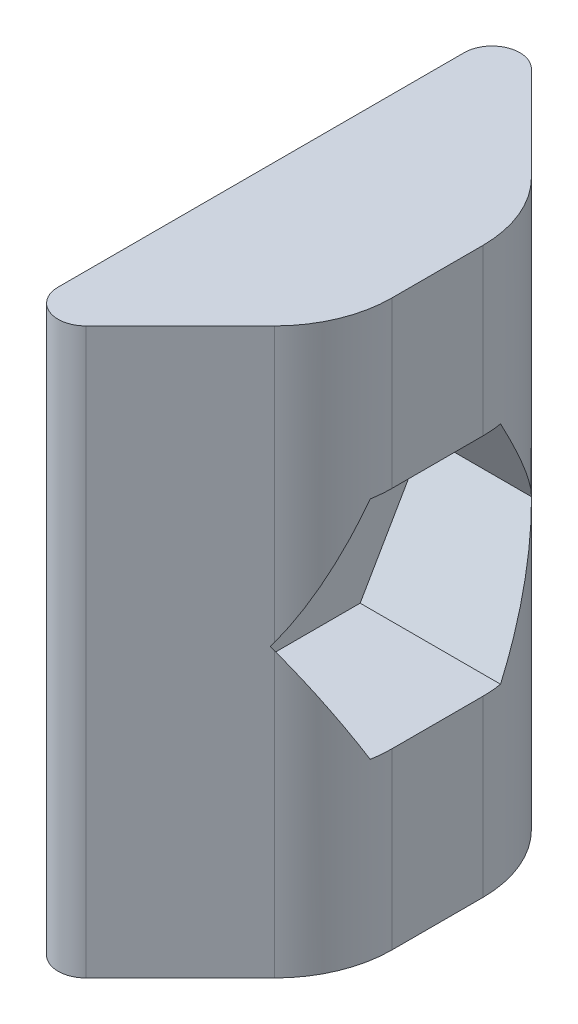
SolidWorks part; units mm, degrees
ref_plane "Front Plane" through (0, 0, 0) normal (0, 0, 1) x (1, 0, 0)
ref_plane "Top Plane" through (0, 0, 0) normal (0, 1, 0) x (1, 0, 0)
ref_plane "Right Plane" through (0, 0, 0) normal (1, 0, 0) x (0, 0, -1)
sketch "Sketch1" plane through (0, 887.3681, 0) normal (0, 1, 0) x (1, 0, 0)
  line L11 (633.4437, -1269.9722) -> (633.4437, -1272.1413) construction
  line L12 (633.4437, -1262.0731) -> (633.4437, -1264.2422) construction
  line L13 (636.9614, -1263.925) -> (634.6216, -1261.5852) construction
  line L14 (637.8137, -1268.2318) -> (637.8137, -1265.9826) construction
  line L15 (634.6216, -1272.6292) -> (636.9614, -1270.2895) construction
  line L16 (633.4437, -1269.9722) -> (633.4437, -1272.1413)
  line L17 (633.4437, -1262.0731) -> (633.4437, -1264.2422)
  line L18 (636.9614, -1263.925) -> (634.6216, -1261.5852)
  line L19 (637.8137, -1268.2318) -> (637.8137, -1265.9826)
  line L20 (634.6216, -1272.6292) -> (636.9614, -1270.2895)
  line L21 (633.4437, -1269.9722) -> (633.4437, -1264.2422)
  line L22 (633.4937, -1269.9722) -> (633.4937, -1264.2422) construction
  line L23 (633.4937, -1262.0731) -> (633.4937, -1264.2422) construction
  line L24 (636.926, -1263.9603) -> (634.5862, -1261.6205) construction
  line L25 (637.7637, -1268.2318) -> (637.7637, -1265.9826) construction
  line L26 (634.5862, -1272.5939) -> (636.926, -1270.2541) construction
  line L27 (633.4937, -1269.9722) -> (633.4937, -1272.1413) construction
  arc A8 (633.4437, -1272.1413) -> (634.6216, -1272.6292) centre (634.1337, -1272.1413) ccw construction
  arc A9 (634.6216, -1261.5852) -> (633.4437, -1262.0731) centre (634.1337, -1262.0731) ccw construction
  arc A10 (637.8137, -1265.9826) -> (636.9614, -1263.925) centre (634.9037, -1265.9826) ccw construction
  arc A11 (636.9614, -1270.2895) -> (637.8137, -1268.2318) centre (634.9037, -1268.2318) ccw construction
  arc A12 (633.4437, -1272.1413) -> (634.6216, -1272.6292) centre (634.1337, -1272.1413) ccw
  arc A13 (634.6216, -1261.5852) -> (633.4437, -1262.0731) centre (634.1337, -1262.0731) ccw
  arc A14 (637.8137, -1265.9826) -> (636.9614, -1263.925) centre (634.9037, -1265.9826) ccw
  arc A15 (636.9614, -1270.2895) -> (637.8137, -1268.2318) centre (634.9037, -1268.2318) ccw
  arc A16 (634.5862, -1261.6205) -> (633.4937, -1262.0731) centre (634.1337, -1262.0731) ccw construction
  arc A17 (637.7637, -1265.9826) -> (636.926, -1263.9603) centre (634.9037, -1265.9826) ccw construction
  arc A18 (636.926, -1270.2541) -> (637.7637, -1268.2318) centre (634.9037, -1268.2318) ccw construction
  arc A19 (633.4937, -1272.1413) -> (634.5862, -1272.5939) centre (634.1337, -1272.1413) ccw construction
  dimension "D1" = 0.05
extrude "Boss-Extrude1" add sketch "Sketch1" along normal mid plane 14 from offset 2.6
sketch "Sketch2" plane through (633.4937, 0, 0) normal (-1, 0, 0) x (0, 0, 1)
  line L0 (1268.6838, 887.3681) -> (1268.726, 887.4411) construction
  line L1 (1265.5488, 887.3681) -> (1268.6838, 887.3681) construction
  line L2 (1263.9813, 890.0831) -> (1265.5488, 887.3681) construction
  line L3 (1265.5067, 892.7251) -> (1263.9813, 890.0831) construction
  line L4 (1265.5488, 892.7981) -> (1265.5067, 892.7251) construction
  line L5 (1268.6838, 892.7981) -> (1265.5488, 892.7981) construction
  line L6 (1270.2513, 890.0831) -> (1268.6838, 892.7981) construction
  line L7 (1268.726, 887.4411) -> (1270.2513, 890.0831) construction
  line L8 (1268.6838, 887.3681) -> (1268.726, 887.4411) construction
  line L9 (1265.5488, 887.3681) -> (1268.6838, 887.3681) construction
  line L10 (1263.9813, 890.0831) -> (1265.5488, 887.3681) construction
  line L11 (1265.5067, 892.7251) -> (1263.9813, 890.0831) construction
  line L12 (1265.5488, 892.7981) -> (1265.5067, 892.7251) construction
  line L13 (1268.6838, 892.7981) -> (1265.5488, 892.7981) construction
  line L14 (1270.2513, 890.0831) -> (1268.6838, 892.7981) construction
  line L15 (1268.726, 887.4411) -> (1270.2513, 890.0831) construction
  line L16 (1268.73, 887.2881) -> (1268.7953, 887.4011)
  line L17 (1268.7953, 887.4011) -> (1270.3437, 890.0831)
  line L18 (1270.3437, 890.0831) -> (1268.73, 892.8781)
  line L19 (1268.73, 892.8781) -> (1265.5026, 892.8781)
  line L20 (1265.5026, 892.8781) -> (1265.4374, 892.7651)
  line L21 (1265.4374, 892.7651) -> (1263.8889, 890.0831)
  line L22 (1263.8889, 890.0831) -> (1265.5026, 887.2881)
  line L23 (1265.5026, 887.2881) -> (1268.73, 887.2881)
  dimension "D1" = 0.08
extrude "Cut-Extrude1" cut sketch "Sketch2" against normal blind 10 from offset 0.8 offset against normal yes
sketch "Sketch3" plane through (633.4937, 0, 0) normal (-1, 0, 0) x (0, 0, 1)
  circle A0 centre (1267.1163, 890.0831) radius 1.75
  dimension "D1" = 3.5
extrude "Cut-Extrude2" cut sketch "Sketch3" against normal mid plane 10
